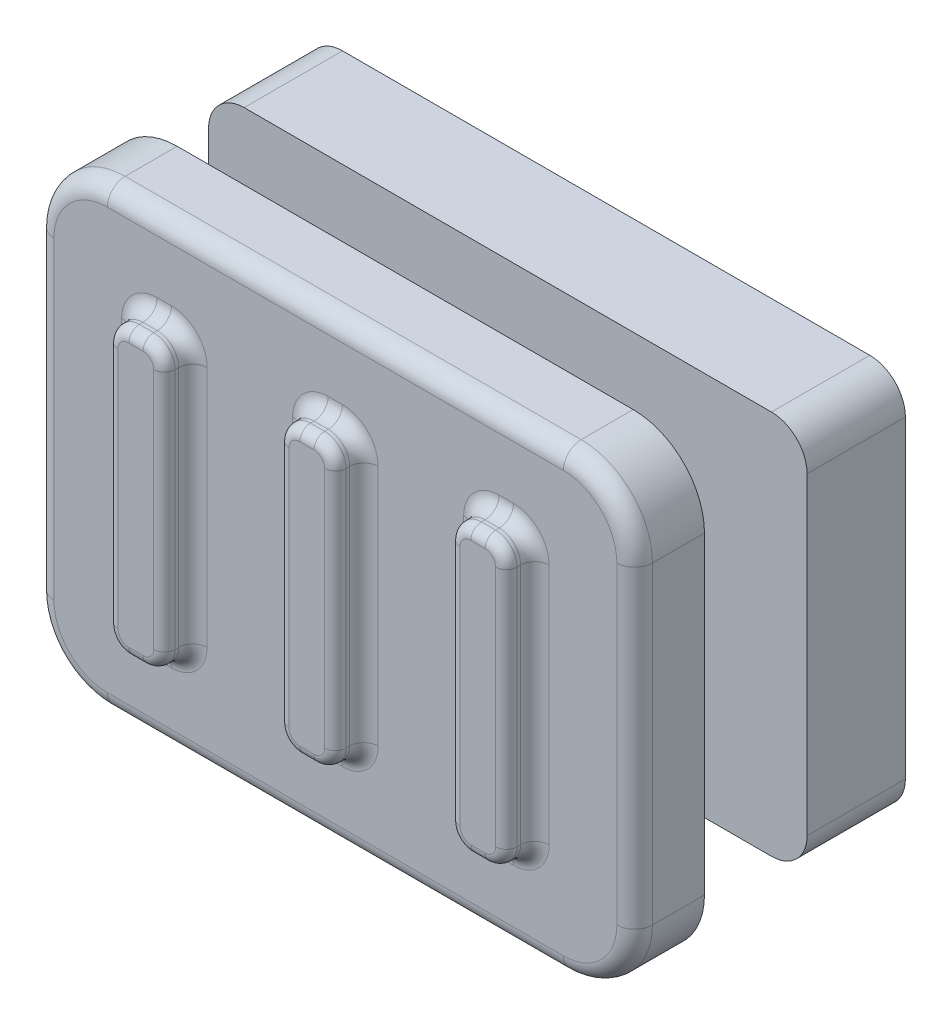
SolidWorks part; units mm, degrees
ref_plane "Спереди" through (0, 0, 0) normal (0, 0, 1) x (1, 0, 0)
ref_plane "Сверху" through (0, 0, 0) normal (0, 1, 0) x (1, 0, 0)
ref_plane "Справа" through (0, 0, 0) normal (1, 0, 0) x (0, 0, -1)
other "Configuration Table"
sketch "Slider_stem_profile" plane through (0, 0, 0) normal (0, 0, 1) x (1, 0, 0)
  line L0 (-1.5, -1.5) -> (1.5, -1.5)
  line L1 (1.9, -1.1) -> (1.9, 1.1)
  line L2 (1.5, 1.5) -> (-1.5, 1.5)
  line L3 (-1.9, 1.1) -> (-1.9, -1.1)
  arc A0 (1.5, -1.5) -> (1.9, -1.1) centre (1.5, -1.1) ccw
  arc A1 (1.9, 1.1) -> (1.5, 1.5) centre (1.5, 1.1) ccw
  arc A2 (-1.5, 1.5) -> (-1.9, 1.1) centre (-1.5, 1.1) ccw
  arc A3 (-1.9, -1.1) -> (-1.5, -1.5) centre (-1.5, -1.1) ccw
extrude "Slider_stem" add sketch "Slider_stem_profile" along normal blind 4.2 from offset 0
sketch "Captive_flange_profile" plane through (0, 0, 0) normal (0, 0, 1) x (1, 0, 0)
  line L0 (-3.7, -2.7) -> (3.7, -2.7)
  line L1 (4.2, -2.2) -> (4.2, 2.2)
  line L2 (3.7, 2.7) -> (-3.7, 2.7)
  line L3 (-4.2, 2.2) -> (-4.2, -2.2)
  arc A0 (3.7, -2.7) -> (4.2, -2.2) centre (3.7, -2.2) ccw
  arc A1 (4.2, 2.2) -> (3.7, 2.7) centre (3.7, 2.2) ccw
  arc A2 (-3.7, 2.7) -> (-4.2, 2.2) centre (-3.7, 2.2) ccw
  arc A3 (-4.2, -2.2) -> (-3.7, -2.7) centre (-3.7, -2.2) ccw
extrude "Captive_flange" add sketch "Captive_flange_profile" along normal blind 1.38 from offset 1.2
sketch "Thumb_pad_profile" plane through (0, 0, 0) normal (0, 0, 1) x (1, 0, 0)
  line L0 (-3.2, -3.2) -> (3.2, -3.2)
  line L1 (4.2, -2.2) -> (4.2, 2.2)
  line L2 (3.2, 3.2) -> (-3.2, 3.2)
  line L3 (-4.2, 2.2) -> (-4.2, -2.2)
  arc A0 (3.2, -3.2) -> (4.2, -2.2) centre (3.2, -2.2) ccw
  arc A1 (4.2, 2.2) -> (3.2, 3.2) centre (3.2, 2.2) ccw
  arc A2 (-3.2, 3.2) -> (-4.2, 2.2) centre (-3.2, 2.2) ccw
  arc A3 (-4.2, -2.2) -> (-3.2, -3.2) centre (-3.2, -2.2) ccw
extrude "Thumb_pad" add sketch "Thumb_pad_profile" along normal blind 0.98 from offset 4.02
sketch "Switch_pin_socket_profile" plane through (0, 0, 0) normal (0, 0, 1) x (1, 0, 0)
  line L0 (-0.725, -0.6) -> (0.725, -0.6)
  line L1 (0.825, -0.5) -> (0.825, 0.5)
  line L2 (0.725, 0.6) -> (-0.725, 0.6)
  line L3 (-0.825, 0.5) -> (-0.825, -0.5)
  arc A0 (0.725, -0.6) -> (0.825, -0.5) centre (0.725, -0.5) ccw
  arc A1 (0.825, 0.5) -> (0.725, 0.6) centre (0.725, 0.5) ccw
  arc A2 (-0.725, 0.6) -> (-0.825, 0.5) centre (-0.725, 0.5) ccw
  arc A3 (-0.825, -0.5) -> (-0.725, -0.6) centre (-0.725, -0.5) ccw
extrude "Switch_pin_socket" cut sketch "Switch_pin_socket_profile" against normal blind 2.4 from offset 2.3
sketch "PCB_edge_relief_profile" plane through (0, 0, 0) normal (0, 0, 1) x (1, 0, 0)
  line L0 (-2, 0.55) -> (2, 0.55)
  line L1 (2, 0.55) -> (2, 1.6)
  line L2 (2, 1.6) -> (-2, 1.6)
  line L3 (-2, 1.6) -> (-2, 0.55)
extrude "PCB_edge_relief" cut sketch "PCB_edge_relief_profile" against normal blind 0.7 from offset 0.6
fillet "Stem_shoulder_round" radius 0.2 24 edges at (1.7828, -1.3828, 1.2) (-1.7828, -1.3828, 1.2) (-1.7828, 1.3828, 1.2) (1.7828, 1.3828, 1.2) (1.7828, -1.3828, 2.58) (-1.7828, -1.3828, 2.58) (-1.7828, 1.3828, 2.58) (1.7828, 1.3828, 2.58) (1.7828, -1.3828, 4.02) (-1.7828, -1.3828, 4.02) (-1.7828, 1.3828, 4.02) (1.7828, 1.3828, 4.02) (0, 1.5, 4.02) (0, 1.5, 1.2) (-1.9, 0, 1.2) (0, -1.5, 1.2) (1.9, 0, 1.2) (0, 1.5, 2.58) (-1.9, 0, 2.58) (-1.9, 0, 4.02) (0, -1.5, 2.58) (0, -1.5, 4.02) (1.9, 0, 2.58) (1.9, 0, 4.02)
sketch "Thumb_rib_0_profile" plane through (0, 0, 0) normal (0, 0, 1) x (1, 0, 0)
  line L0 (-2.5, -2) -> (-2.3, -2)
  line L1 (-2, -1.7) -> (-2, 1.7)
  line L2 (-2.3, 2) -> (-2.5, 2)
  line L3 (-2.8, 1.7) -> (-2.8, -1.7)
  arc A0 (-2.3, -2) -> (-2, -1.7) centre (-2.3, -1.7) ccw
  arc A1 (-2, 1.7) -> (-2.3, 2) centre (-2.3, 1.7) ccw
  arc A2 (-2.5, 2) -> (-2.8, 1.7) centre (-2.5, 1.7) ccw
  arc A3 (-2.8, -1.7) -> (-2.5, -2) centre (-2.5, -1.7) ccw
extrude "Thumb_rib_0" add sketch "Thumb_rib_0_profile" along normal blind 0.5 from offset 4.9
sketch "Thumb_rib_1_profile" plane through (0, 0, 0) normal (0, 0, 1) x (1, 0, 0)
  line L0 (-0.1, -2) -> (0.1, -2)
  line L1 (0.4, -1.7) -> (0.4, 1.7)
  line L2 (0.1, 2) -> (-0.1, 2)
  line L3 (-0.4, 1.7) -> (-0.4, -1.7)
  arc A0 (0.1, -2) -> (0.4, -1.7) centre (0.1, -1.7) ccw
  arc A1 (0.4, 1.7) -> (0.1, 2) centre (0.1, 1.7) ccw
  arc A2 (-0.1, 2) -> (-0.4, 1.7) centre (-0.1, 1.7) ccw
  arc A3 (-0.4, -1.7) -> (-0.1, -2) centre (-0.1, -1.7) ccw
extrude "Thumb_rib_1" add sketch "Thumb_rib_1_profile" along normal blind 0.5 from offset 4.9
sketch "Thumb_rib_2_profile" plane through (0, 0, 0) normal (0, 0, 1) x (1, 0, 0)
  line L0 (2.3, -2) -> (2.5, -2)
  line L1 (2.8, -1.7) -> (2.8, 1.7)
  line L2 (2.5, 2) -> (2.3, 2)
  line L3 (2, 1.7) -> (2, -1.7)
  arc A0 (2.5, -2) -> (2.8, -1.7) centre (2.5, -1.7) ccw
  arc A1 (2.8, 1.7) -> (2.5, 2) centre (2.5, 1.7) ccw
  arc A2 (2.3, 2) -> (2, 1.7) centre (2.3, 1.7) ccw
  arc A3 (2, -1.7) -> (2.3, -2) centre (2.3, -1.7) ccw
extrude "Thumb_rib_2" add sketch "Thumb_rib_2_profile" along normal blind 0.5 from offset 4.9
fillet "Thumb_rib_root_round" radius 0.2 24 edges at (2.0879, -1.9121, 5) (2.4, -2, 5) (2.7121, -1.9121, 5) (2.7121, 1.9121, 5) (2.4, 2, 5) (2.0879, 1.9121, 5) (-0.3121, -1.9121, 5) (0, -2, 5) (0.3121, -1.9121, 5) (0.3121, 1.9121, 5) (0, 2, 5) (-0.3121, 1.9121, 5) (-2.7121, -1.9121, 5) (-2.4, -2, 5) (-2.0879, -1.9121, 5) (-2.0879, 1.9121, 5) (-2.4, 2, 5) (-2.7121, 1.9121, 5) (2.8, 0, 5) (2, 0, 5) (0.4, 0, 5) (-0.4, 0, 5) (-2, 0, 5) (-2.8, 0, 5)
fillet "Thumb_pad_edge_round" radius 0.25 8 edges at (4.2, 0, 5) (3.9071, -2.9071, 5) (3.9071, 2.9071, 5) (0, -3.2, 5) (0, 3.2, 5) (-3.9071, -2.9071, 5) (-3.9071, 2.9071, 5) (-4.2, 0, 5)
fillet "Thumb_rib_crown_round" radius 0.15 24 edges at (2.8, 0, 5.4) (2.7121, 1.9121, 5.4) (2.7121, -1.9121, 5.4) (2.4, 2, 5.4) (2.4, -2, 5.4) (2.0879, 1.9121, 5.4) (2.0879, -1.9121, 5.4) (2, 0, 5.4) (0.4, 0, 5.4) (0.3121, 1.9121, 5.4) (0.3121, -1.9121, 5.4) (0, 2, 5.4) (0, -2, 5.4) (-0.3121, 1.9121, 5.4) (-0.3121, -1.9121, 5.4) (-0.4, 0, 5.4) (-2, 0, 5.4) (-2.0879, 1.9121, 5.4) (-2.0879, -1.9121, 5.4) (-2.4, 2, 5.4) (-2.4, -2, 5.4) (-2.7121, 1.9121, 5.4) (-2.7121, -1.9121, 5.4) (-2.8, 0, 5.4)
